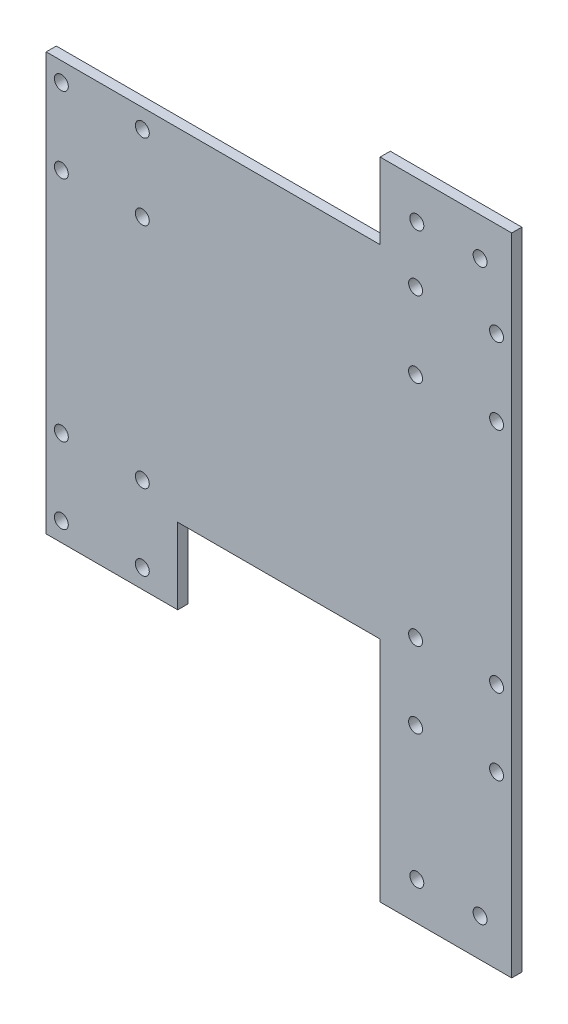
SolidWorks part; units mm, degrees
ref_plane "Front Plane" through (0, 0, 0) normal (0, 0, 1) x (1, 0, 0)
ref_plane "Top Plane" through (0, 0, 0) normal (0, 1, 0) x (1, 0, 0)
ref_plane "Right Plane" through (0, 0, 0) normal (1, 0, 0) x (0, 0, -1)
sketch "Sketch1" plane through (0, 0, 0) normal (0, 0, 1) x (1, 0, 0)
  line L1 (-22, -22.5) -> (162, -22.5)
  line L2 (-22, -22.5) -> (-22, 142.5)
  line L3 (-22, 142.5) -> (162, 142.5)
  line L4 (162, -22.5) -> (162, 142.5)
extrude "Boss-Extrude1" add sketch "Sketch1" along normal blind 4
hole_wizard "M5 Clearance Hole1" positions "Sketch3" profile "Sketch2" hole size "M5" standard "ISO" end condition through all
sketch "Sketch3" plane through (0, 0, 0) normal (0, 0, -1) x (-1, 0, 0)
  point P0 (-16, -15)
  point P3 (-16, 15)
  point P6 (16, 15)
  point P9 (16, -15)
  point P12 (16, 105)
  point P15 (-16, 105)
  point P18 (-16, 135)
  point P21 (16, 135)
  point P24 (-124, 135)
  point P27 (-124, 105)
  point P30 (-156, 105)
  point P33 (-156, 135)
  point P36 (-156, 15)
  point P39 (-124, 15)
  point P42 (-124, -15)
  point P45 (-156, -15)
sketch "Sketch2" plane through (16, -15, 0) normal (1, 0, 0) x (0, 1, 0)
  line L0 (0, 0) -> (0, 4)
  line L1 (0, 4) -> (2.75, 4)
  line L2 (2.75, 4) -> (2.75, 0)
  line L5 (2.75, 0) -> (0, 0)
  line L11 (0, -6.35) -> (0, 107.95) construction
  dimension "Thru Hole Dia." = 5.5
  dimension "Thru Hole Depth" = 4
sketch "Sketch4" plane through (0, 0, 4) normal (0, 0, 1) x (1, 0, 0)
  line L1 (70, -22.5) -> (70, 7.5) construction
  line L2 (-22, -22.5) -> (162, -22.5) construction
  line L4 (30, -22.5) -> (110, -22.5)
  line L5 (30, -22.5) -> (30, 7.5)
  line L7 (30, 7.5) -> (110, 7.5)
  line L8 (110, -22.5) -> (110, 7.5)
  dimension "D1" = 80
  dimension "D2" = 30
extrude "Cut-Extrude1" cut sketch "Sketch4" against normal blind 10
sketch "Sketch5" plane through (0, 0, 4) normal (0, 0, 1) x (1, 0, 0)
  line L0 (110, -22.5) -> (110, 7.5) construction
  line L1 (162, -22.5) -> (110, -22.5)
  line L2 (162, -22.5) -> (162, -82.5)
  line L3 (162, -82.5) -> (110, -82.5)
  line L4 (110, -22.5) -> (110, -82.5)
  line L6 (162, 142.5) -> (110, 142.5)
  line L7 (162, 142.5) -> (162, 172.5)
  line L8 (162, 172.5) -> (110, 172.5)
  line L9 (110, 142.5) -> (110, 172.5)
  dimension "D1" = 60
  dimension "D2" = 30
extrude "Boss-Extrude2" add sketch "Sketch5" against normal up to surface (4 mm away) up to face at (70, 26.25, 0)
hole_wizard "M5 Clearance Hole2" positions "Sketch8" profile "Sketch7" hole size "M5" standard "ISO" end condition through all
sketch "Sketch8" plane through (0, 0, 4) normal (0, 0, 1) x (1, 0, 0)
  line L13 (61.9164, 45) -> (162, 45) construction
  line L14 (137, -39.999) -> (137, 180.0985) construction
  line L16 (162, -82.5) -> (162, 172.5) construction
  line L17 (110, -82.5) -> (162, -82.5) construction
  point P2 (149.5, -67.5)
  point P77 (124.5, -67.5)
  point P232 (124.5, 157.5)
  point P234 (149.5, 157.5)
  dimension "D1" = 25
  dimension "D2" = 25
  dimension "D3" = 15
sketch "Sketch7" plane through (149.5, -67.5, 4) normal (1, 0, 0) x (0, -1, 0)
  line L0 (0, 0) -> (0, 4)
  line L1 (0, 4) -> (2.75, 4)
  line L2 (2.75, 4) -> (2.75, 0)
  line L5 (2.75, 0) -> (0, 0)
  line L11 (0, -6.35) -> (0, 107.95) construction
  dimension "Thru Hole Dia." = 5.5
  dimension "Thru Hole Depth" = 4
